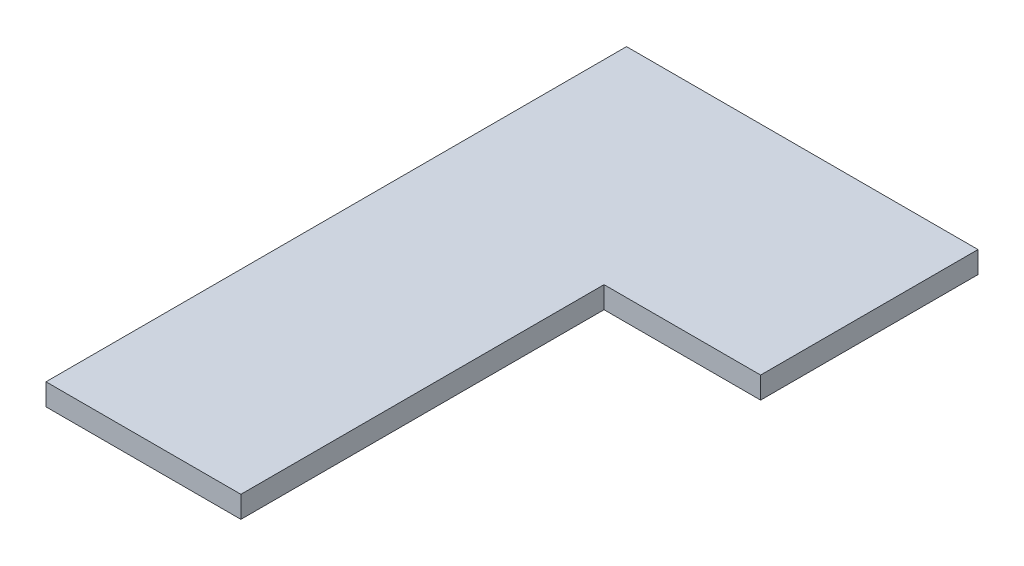
SolidWorks part; units mm, degrees
ref_plane "前视基准面" through (0, 0, 0) normal (0, 0, 1) x (1, 0, 0)
ref_plane "上视基准面" through (0, 0, 0) normal (0, 1, 0) x (1, 0, 0)
ref_plane "右视基准面" through (0, 0, 0) normal (1, 0, 0) x (0, 0, -1)
other "Configuration Table"
sketch "草图1" plane through (0, 0, 0) normal (0, 1, 0) x (1, 0, 0)
  line L0 (0, 0) -> (-48.5057, 0)
  line L1 (-48.5057, 0) -> (-48.5057, -80.1149)
  line L2 (-48.5057, -80.1149) -> (-21.6092, -80.1149)
  line L3 (-21.6092, -80.1149) -> (-21.6092, -30)
  line L4 (-21.6092, -30) -> (0, -30)
  line L5 (0, -30) -> (0, 0)
  dimension "D1" = 30
extrude "凸台-拉伸1" add sketch "草图1" along normal blind 3
